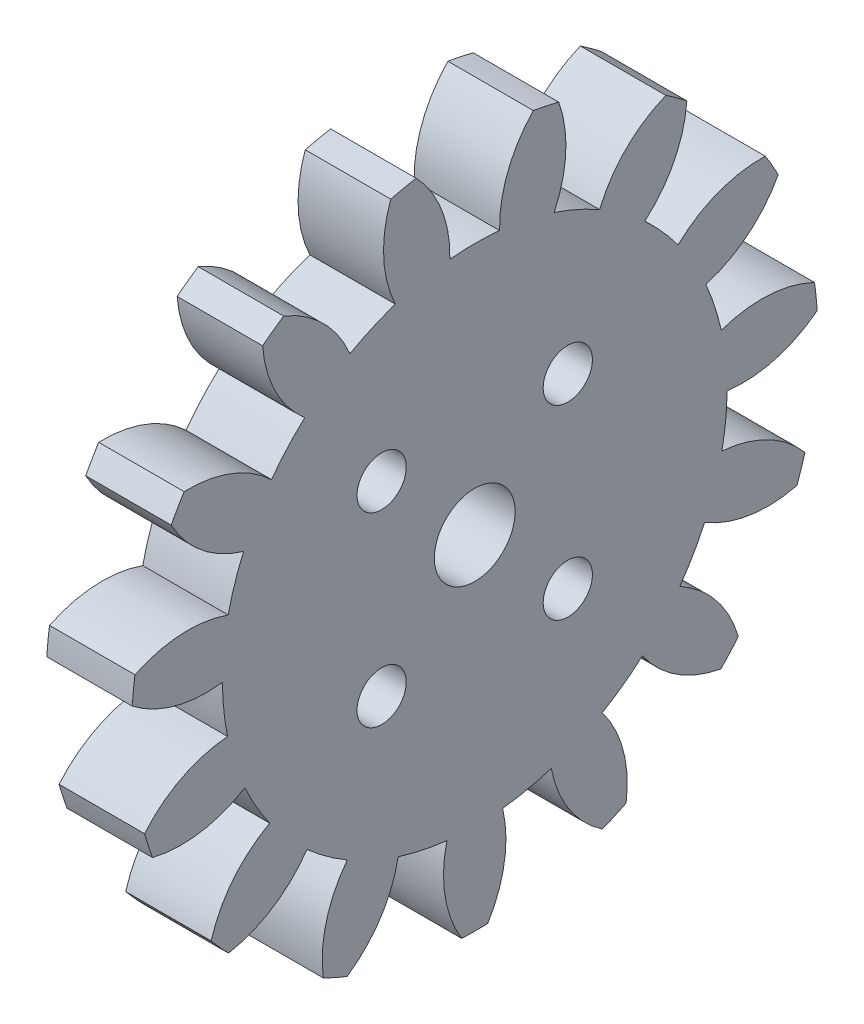
SolidWorks part; units mm, degrees
ref_plane "Plane1" through (0, 0, 0) normal (0, 0, 1) x (1, 0, 0)
ref_plane "Plane2" through (0, 0, 0) normal (0, 1, 0) x (1, 0, 0)
ref_plane "Plane3" through (0, 0, 0) normal (1, 0, 0) x (0, 0, -1)
sketch "HoldingSke" plane through (0, 0, 0) normal (0, 1, 0) x (1, 0, 0)
  line L0 (0, 0) -> (0.322, -0.0863)
  line L1 (-15, 0) -> (100, 0) construction
  line L2 (0, 0) -> (-2.1039, 2.3779)
  line L3 (0, 0) -> (-11.863, 4.5341)
  line L4 (0, 0) -> (8.3417, 2.2352)
  line L5 (0, 0) -> (-46.8476, -17.4728)
  line L6 (0, 0) -> (-5.2639, -3.5516)
  line L7 (-2.1039, 2.3779) -> (8.6586, 51.2059)
  line L8 (-76.2, 54.61) -> (-75.2, 54.61)
  line L9 (-67.7845, 28.3722) -> (-49.3413, 33.142)
  line L10 (-76.2, 71.12) -> (104.1128, 71.12)
  line L11 (0, 0) -> (-6.35, 0)
  line L12 (-76.2, 101.6) -> (-76.093, 101.6)
  line L13 (24.9733, 27.94) -> (52.9518, 28.4284)
  line L14 (24.9733, 27.94) -> (24.9743, 27.94)
  line L15 (24.9733, 27.94) -> (100.4006, 29.5858)
  line L16 (-63.627, -3) -> (-12.827, -3)
  circle A0 centre (0, 0) radius 3
  circle A1 centre (0, 0) radius 18.749
  circle A2 centre (0, 0) radius 37.5
  circle A3 centre (0, 0) radius 3
  dimension "MHD" = 37.498
  dimension "Hub_dia" = 75
  dimension "Bore" = 6
  dimension "MBD" = 6
  dimension "Num_teeth" = 15
  dimension "Pitch" = 0.3333
  dimension "Overall_len" = 50
  dimension "Show_teeth" = 15
  dimension "Thickness" = 6.35
  dimension "OAL" = 50.0001
  dimension "T_dim" = 1
  dimension "Ap" = 14.5
  dimension "H" = 19.05
  dimension "Pitch_radius" = 180.3128
  dimension "Width" = 6.35
  dimension "Backlash" = 0.107
  dimension "Addendum_fac" = 1
  dimension "Dedendum_fac" = 1.25
  dimension "Clearance_fac" = 0.25
  dimension "Dedendum_add" = 0.001
  dimension "Module" = 3
sketch "BasProSke" plane through (0, 0, 0) normal (0, 1, 0) x (1, 0, 0)
  line L0 (-10, 0) -> (60, 0) construction
  line L1 (0, 0) -> (0, 25.5)
  line L2 (0, 0) -> (6.35, 0)
  line L3 (6.35, 0) -> (6.35, 25.5)
  line L4 (6.35, 25.5) -> (0, 25.5)
  dimension "Thickness" = 6.35
  dimension "Diameter" = 51
revolve "Base-Revolve" add sketch "BasProSke" angle 360 about L0
sketch "TooCutSke" plane through (0, 0, 0) normal (1, 0, 0) x (0, 0, -1)
  line L1 (0, 0) -> (0, 107) construction
  line L2 (0, 0) -> (-2.539, 22.3563) construction
  line L3 (0, 0) -> (-9.3126, 43.8125) construction
  line L4 (-2.539, 22.3563) -> (-4.6563, 21.9062) construction
  arc A0 (1.8484, 18.6577) -> (-1.8484, 18.6577) centre (0, 0) ccw
  arc A1 (4.3753, 25.1476) -> (-4.3753, 25.1476) centre (0, 0) ccw
  circle A2 centre (0, 0) radius 22.5 construction
  circle A3 centre (0, 0) radius 21.7833 construction
  arc A4 (-1.8484, 18.6577) -> (-4.3753, 25.1476) centre (-10.8453, 18.8916) ccw
  arc A5 (4.3753, 25.1476) -> (1.8484, 18.6577) centre (10.8453, 18.8916) ccw
  dimension "Root_dia" = 37.498
  dimension "Overcut_dia" = 51.0508
  dimension "Pitch_dia" = 45
  dimension "Base_dia" = 43.5666
  dimension "Flank_rad" = 9
  dimension "Half_ang" = 12
  dimension "Half_CT" = 2.1646
extrude "ToothCut" cut sketch "TooCutSke" along normal through all
fillet "Breaks" [suppressed] radius 0.06
fillet "RootFillets" [suppressed] radius 0.751
pattern_circular "TeethCuts" count 15 every 24 about axis through (-10, 0, 0) along (1, 0, 0) of "ToothCut", "RootFillets", "Breaks"
sketch "HubNeaOneSke" plane through (0, 0, 0) normal (-1, 0, 0) x (0, 0, 1)
  circle A0 centre (0, 0) radius 18.749
  dimension "Diameter" = 37.498
extrude "HubNearOne" [suppressed] add sketch "HubNeaOneSke" along normal blind 43.6501
sketch "HubNeaBotSke" plane through (0, 0, 0) normal (-1, 0, 0) x (0, 0, 1)
  circle A0 centre (0, 0) radius 18.749
  dimension "Diameter" = 37.498
extrude "HubNearBoth" [suppressed] add sketch "HubNeaBotSke" along normal blind 21.825
ref_plane "FarPln" through (6.35, 0, 0) normal (1, 0, 0) x (0, 0, -1)
sketch "HubFarSke" plane through (6.35, 0, 0) normal (1, 0, 0) x (0, 0, -1)
  circle A0 centre (0, 0) radius 18.749
  dimension "Diameter" = 37.498
extrude "HubFar" [suppressed] add sketch "HubFarSke" along normal blind 21.825
sketch "BorSke" plane through (0, 0, 0) normal (1, 0, 0) x (0, 0, -1)
  circle A0 centre (0, 0) radius 3
  dimension "Diameter" = 6
extrude "Bore" cut sketch "BorSke" along normal mid plane 100.0001
sketch "KeySke" plane through (0, 0, 0) normal (1, 0, 0) x (0, 0, -1)
  line L0 (-1, 0) -> (-1, 4)
  line L1 (-1, 4) -> (1, 4)
  line L2 (1, 4) -> (1, 0)
  line L3 (0, 0) -> (0, 34) construction
  line L4 (-1, 0) -> (1, 0)
  dimension "Offset" = 4
  dimension "Width" = 2
extrude "Keyway" [suppressed] cut sketch "KeySke" along normal mid plane 100.0001
pattern_circular "Keyway2" [suppressed] count 2 every 90 about axis through (-10, 0, 0) along (1, 0, 0)
sketch "Esquisse1" plane through (0, 0, 0) normal (-1, 0, 0) x (0, 0, 1)
  circle A0 centre (-6.9148, 6.9148) radius 1.83
  dimension "D1" = 3.66
extrude "Enlèv. mat.-Extru.1" cut sketch "Esquisse1" against normal up to next
pattern_circular "Répétition circulaire1" count 4 every 90 about axis through (0, 0, 0) along (1, 0, 0) of "Enlèv. mat.-Extru.1"
equation "' \"Module@HoldingSke\" = 6.35"
equation "' \"Num_teeth@HoldingSke\" = 12"
equation "' \"Ap@HoldingSke\" =  20"
equation "' \"Ap@HoldingSke\" = 20"
equation "' \"Width@HoldingSke\" = 0.5 * 25.4"
equation "' \"Hub_dia@HoldingSke\"= 1 * 25.4"
equation "' \"Hub_dia@HoldingSke\" = 1 * 25.4"
equation "' \"Overall_len@HoldingSke\" = 1.0 * 25.4"
equation "' \"Bore@HoldingSke\" = 0.75 * 25.4"
equation "' \"T_dim@HoldingSke\" = 0.1 * 25.4"
equation "' \"Width@KeySke\" = 0.25 * 25.4"
equation "' \"Show_teeth@HoldingSke\" = 13"
equation "' \"Backlash@HoldingSke\" = 0.009 * 25.4"
equation "' \"Addendum_fac@HoldingSke\" = 1.0"
equation "' \"Dedendum_fac@HoldingSke\" = 1.25"
equation "' \"Dedendum_add@HoldingSke\" = 0.00005 * 25.4"
equation "' \"Clearance_fac@HoldingSke\" = 0.25"
equation "\"Pitch@HoldingSke\" = 1 / \"Module@HoldingSke\""
equation "\"Overcut_dia@TooCutSke\" = (\"Num_teeth@HoldingSke\" + 2 * \"Addendum_fac@HoldingSke\") / \"Pitch@HoldingSke\" + 0.002 * 25.4"
equation "\"Pitch_dia@TooCutSke\" = \"Num_teeth@HoldingSke\" / \"Pitch@HoldingSke\""
equation "\"Base_dia@TooCutSke\" = \"Num_teeth@HoldingSke\" / \"Pitch@HoldingSke\" * cos((\"Ap@HoldingSke\"  * 3.14159265 / 180))"
equation "\"Root_dia@TooCutSke\" = (\"Num_teeth@HoldingSke\" + 2) / \"Pitch@HoldingSke\" - 2 * (\"Addendum_fac@HoldingSke\" + \"Dedendum_fac@HoldingSke\") / \"Pitch@HoldingSke\" - \"Dedendum_add@HoldingSke\" * 2"
equation "\"Half_ang@TooCutSke\" = 180 / \"Num_teeth@HoldingSke\""
equation "\"Half_CT@TooCutSke\" = \"Num_teeth@HoldingSke\" / \"Pitch@HoldingSke\" * sin((3.14159265 / 2 / \"Num_teeth@HoldingSke\")) / 2 - 7 * \"Backlash@HoldingSke\" / 4"
equation "\"Flank_rad@TooCutSke\" = \"Num_teeth@HoldingSke\" / \"Pitch@HoldingSke\" / 5"
equation "\"Radius@RootFillets\" = \"Clearance_fac@HoldingSke\" / \"Pitch@HoldingSke\" + \"Dedendum_add@HoldingSke\""
equation "\"Break_rad@Breaks\" = 0.02 / \"Pitch@HoldingSke\""
equation "\"Thickness@HoldingSke\" = \"Width@HoldingSke\""
equation "\"OAL@HoldingSke\" = \"Thickness@HoldingSke\""
equation "\"MHD@HoldingSke\" = (\"Num_teeth@HoldingSke\" + 2) / \"Pitch@HoldingSke\" - 2 * (\"Addendum_fac@HoldingSke\" + \"Dedendum_fac@HoldingSke\")  / \"Pitch@HoldingSke\" - \"Dedendum_add@HoldingSke\" * 2"
equation "\"MBD@HoldingSke\" = (\"Num_teeth@HoldingSke\" + 2) / \"Pitch@HoldingSke\" - 2 * (\"Addendum_fac@HoldingSke\" + \"Dedendum_fac@HoldingSke\")  / \"Pitch@HoldingSke\" - \"Dedendum_add@HoldingSke\" * 2 - 0.002 * 25.4"
equation "\"MHD@HoldingSke\" = ((sgn( \"MHD@HoldingSke\" - \"Hub_dia@HoldingSke\" )-1)*( \"MHD@HoldingSke\" - \"Hub_dia@HoldingSke\" ))/-2+ \"Hub_dia@HoldingSke\""
equation "\"MBD@HoldingSke\" = ((sgn( \"MBD@HoldingSke\" - \"Bore@HoldingSke\" )-1)*( \"MBD@HoldingSke\" - \"Bore@HoldingSke\" ))/-2+ \"Bore@HoldingSke\""
equation "\"OAL@HoldingSke\" = ((sgn( \"OAL@HoldingSke\" - \"Overall_len@HoldingSke\" )+1)*( \"OAL@HoldingSke\" - \"Overall_len@HoldingSke\" ))/2 + \"Overall_len@HoldingSke\" + 0.000002 * 25.4"
equation "\"Num_teeth@TeethCuts\" = int( \"Show_teeth@HoldingSke\" ) + 1"
equation "\"Num_teeth@TeethCuts\" = ((sgn( \"Num_teeth@TeethCuts\" - \"Num_teeth@HoldingSke\" )-1)*( \"Num_teeth@TeethCuts\" - \"Num_teeth@HoldingSke\" ))/-2+ \"Num_teeth@HoldingSke\""
equation "\"Num_teeth@TeethCuts\" = ((sgn( \"Num_teeth@TeethCuts\" - 2.0)+1)*( \"Num_teeth@TeethCuts\" - 2.0))/2 +2.0"
equation "\"Angle@TeethCuts\" = 360.0 / \"Num_teeth@HoldingSke\""
equation "\"Diameter@BasProSke\" = (\"Num_teeth@HoldingSke\" + 2 * \"Addendum_fac@HoldingSke\") / \"Pitch@HoldingSke\""
equation "\"Thickness@BasProSke\"  = \"Thickness@HoldingSke\""
equation "' \"Fillet_rad@BasProSke\" =  \"Thickness@HoldingSke\" * 0.05"
equation "' \"Fillet_rad@BasProSke\" = \"Thickness@HoldingSke\" * 0.05"
equation "\"MHD@HoldingSke\" = ((sgn( \"MHD@HoldingSke\" - \"Root_dia@TooCutSke\" )-1)*( \"MHD@HoldingSke\" - \"Root_dia@TooCutSke\" ))/-2+ \"Root_dia@TooCutSke\""
equation "\"Diameter@HubNeaOneSke\" = \"MHD@HoldingSke\""
equation "\"Length@HubNearOne\" = \"OAL@HoldingSke\" - \"Thickness@BasProSke\""
equation "\"Diameter@HubNeaBotSke\" = \"MHD@HoldingSke\""
equation "\"Length@HubNearBoth\" = ( \"OAL@HoldingSke\" - \"Thickness@BasProSke\" ) / 2.0"
equation "\"Thickness@FarPln\" = \"Thickness@BasProSke\""
equation "\"Diameter@HubFarSke\" = \"MHD@HoldingSke\""
equation "\"Length@HubFar\" = ( \"OAL@HoldingSke\" - \"Thickness@BasProSke\" ) / 2.0"
equation "\"Diameter@BorSke\" = \"MBD@HoldingSke\""
equation "\"D1@Bore\" = \"OAL@HoldingSke\" * 2.0"
equation "\"D1@Keyway\" = \"OAL@HoldingSke\" * 2.0"
equation "\"Offset@KeySke\" = \"T_dim@HoldingSke\" + \"MBD@HoldingSke\" / 2.0"
